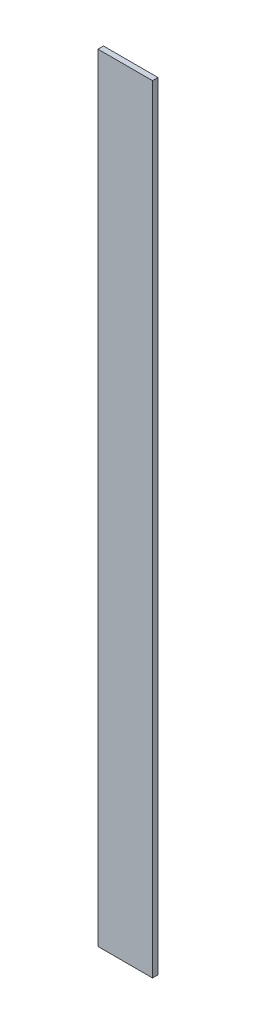
SolidWorks part; units mm, degrees
ref_plane "Front Plane" through (0, 0, 0) normal (0, 0, 1) x (1, 0, 0)
ref_plane "Top Plane" through (0, 0, 0) normal (0, 1, 0) x (1, 0, 0)
ref_plane "Right Plane" through (0, 0, 0) normal (1, 0, 0) x (0, 0, -1)
sketch "Sketch1" plane through (0, 0, 0) normal (0, 0, 1) x (1, 0, 0)
  line L1 (0, 0) -> (31.575, 0)
  line L2 (0, 0) -> (0, 450)
  line L3 (0, 450) -> (31.575, 450)
  line L4 (31.575, 0) -> (31.575, 450)
  dimension "D1" = 450
  dimension "D2" = 31.575
extrude "Boss-Extrude1" add sketch "Sketch1" along normal blind 3.175
